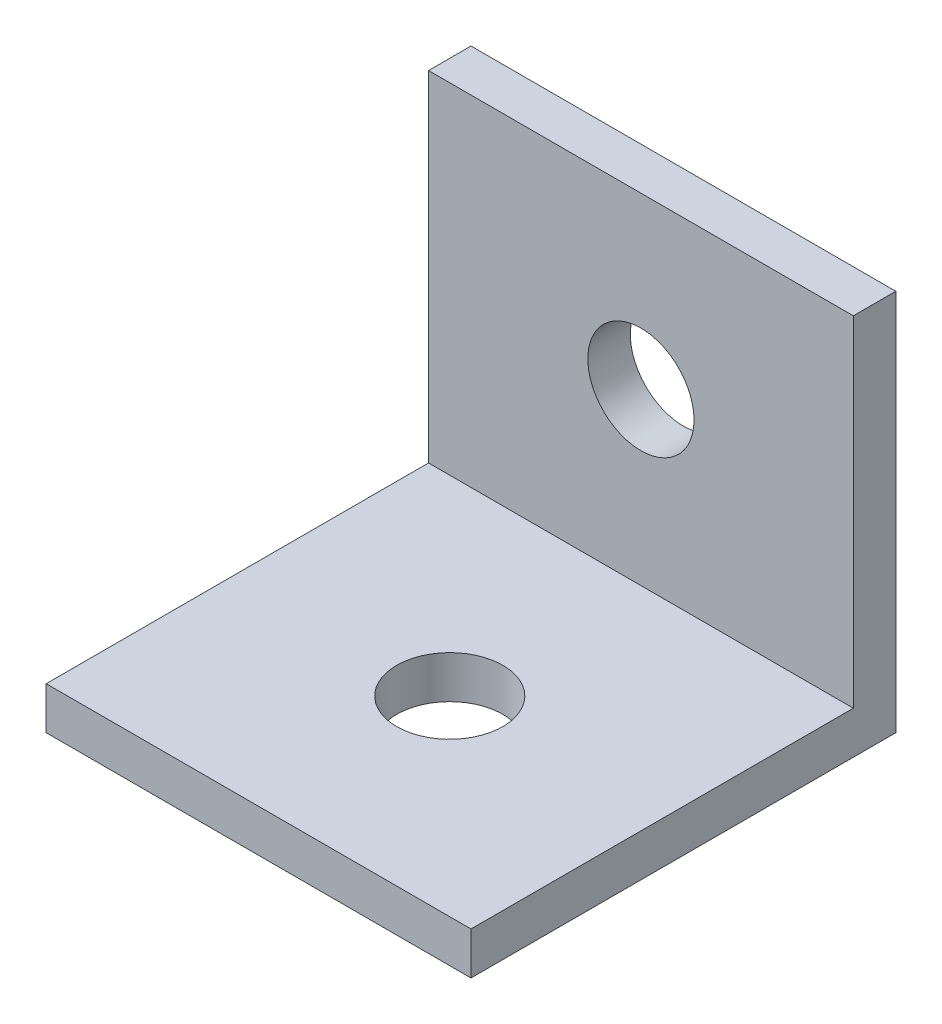
SolidWorks part; units mm, degrees
ref_plane "Front Plane" through (0, 0, 0) normal (0, 0, 1) x (1, 0, 0)
ref_plane "Top Plane" through (0, 0, 0) normal (0, 1, 0) x (1, 0, 0)
ref_plane "Right Plane" through (0, 0, 0) normal (1, 0, 0) x (0, 0, -1)
sketch "Sketch1" plane through (0, 0, 0) normal (0, 1, 0) x (1, 0, 0)
  line L1 (10, -10) -> (-10, -10)
  line L2 (10, -10) -> (10, 10)
  line L3 (10, 10) -> (-10, 10)
  line L4 (-10, -10) -> (-10, 10)
  line L5 (10, -10) -> (-10, 10) construction
  line L6 (10, 10) -> (-10, -10) construction
  point P0 (0, 0)
  dimension "D1" = 20
  dimension "D2" = 20
extrude "Boss-Extrude1" add sketch "Sketch1" along normal blind 2
sketch "Sketch2" plane through (0, 2, 0) normal (0, 1, 0) x (1, 0, 0)
  line L0 (10, -10) -> (10, 10) construction
  line L1 (-10, 10) -> (10, 10)
  line L2 (-10, 10) -> (-10, 8)
  line L3 (-10, 8) -> (10, 8)
  line L4 (10, 10) -> (10, 8)
  dimension "D1" = 2
extrude "Boss-Extrude2" add sketch "Sketch2" along normal blind 16
sketch "Sketch3" plane through (0, 2, 0) normal (0, 1, 0) x (1, 0, 0)
  line L0 (-10, -1) -> (0, -1) construction
  line L3 (-10, 8) -> (-10, -10) construction
  line L4 (0, -1) -> (10, -1) construction
  line L5 (10, -10) -> (10, 8) construction
  circle A0 centre (0, -1) radius 2.5
  dimension "D1" = 5
extrude "Cut-Extrude1" cut sketch "Sketch3" against normal through all
sketch "Sketch4" plane through (0, 0, -8) normal (0, 0, 1) x (1, 0, 0)
  line L0 (10, 10) -> (-10, 10) construction
  line L1 (10, 18) -> (10, 2) construction
  line L2 (-10, 18) -> (-10, 2) construction
  circle A0 centre (0, 10) radius 2.5
  point P8 (0, 0)
  dimension "D1" = 5
extrude "Cut-Extrude2" cut sketch "Sketch4" against normal through all
